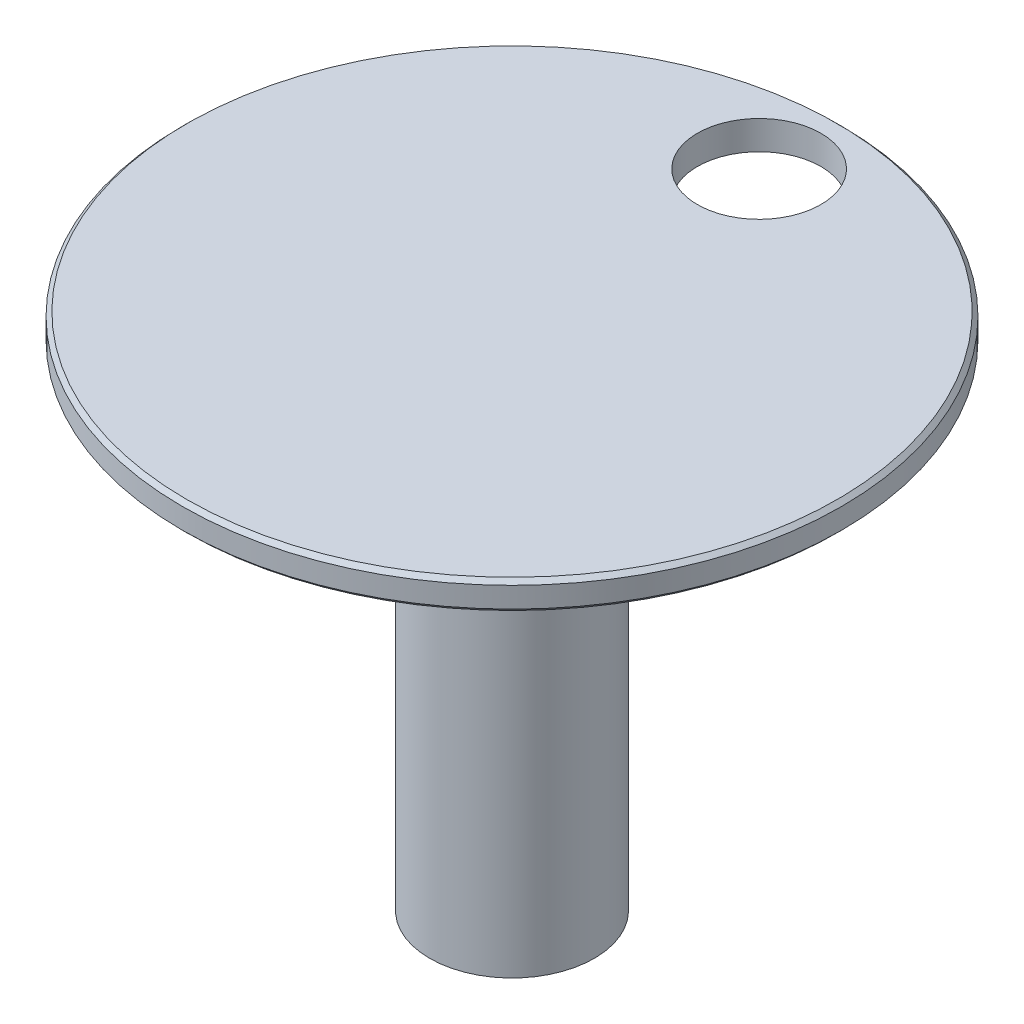
SolidWorks part; units mm, degrees
ref_plane "Front Plane" through (0, 0, 0) normal (0, 0, 1) x (1, 0, 0)
ref_plane "Top Plane" through (0, 0, 0) normal (0, 1, 0) x (1, 0, 0)
ref_plane "Right Plane" through (0, 0, 0) normal (1, 0, 0) x (0, 0, -1)
sketch "Sketch2" plane through (0, 0, 0) normal (0, 1, 0) x (1, 0, 0)
  circle A0 centre (0, 0) radius 2
extrude "Boss-Extrude1" add sketch "Sketch2" along normal blind 11.6
sketch "Sketch3" plane through (0, 11.6, 0) normal (0, 1, 0) x (1, 0, 0)
  circle A0 centre (0, 0) radius 4
extrude "Boss-Extrude2" add sketch "Sketch3" along normal blind 0.3
sketch "Sketch4" plane through (0, 11.9, 0) normal (0, 1, 0) x (1, 0, 0)
  circle A0 centre (0, 0) radius 8
extrude "Boss-Extrude3" add sketch "Sketch4" along normal blind 0.7
sketch "Sketch5" plane through (0, 0, 0) normal (0, -1, 0) x (1, 0, 0)
  circle A0 centre (0, 0) radius 1.5
extrude "Cut-Extrude1" cut sketch "Sketch5" against normal blind 8.5
sketch "Sketch6" plane through (0, 11.9, 0) normal (0, -1, 0) x (1, 0, 0)
  circle A0 centre (0, -6) radius 1.5
  dimension "D1" = 6
extrude "Cut-Extrude2" cut sketch "Sketch6" against normal through all
chamfer "Chamfer1" distance 0.1 angle 45 2 edges at (0, 11.9, 8) (0, 12.6, 8)
